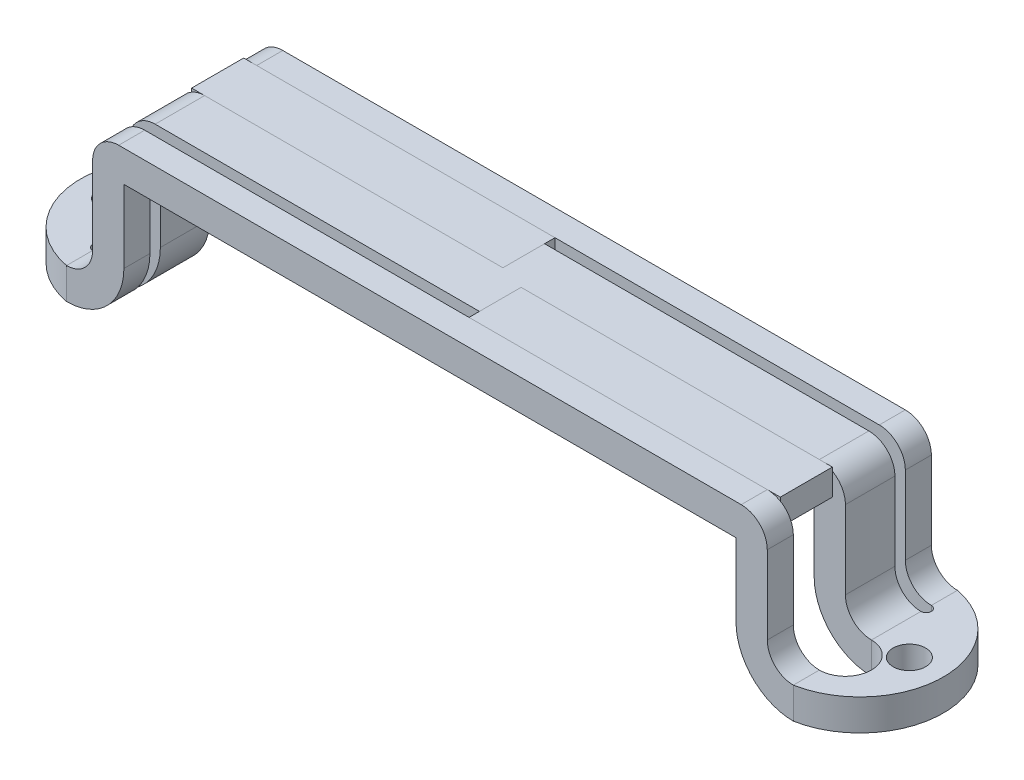
SolidWorks part; units mm, degrees
ref_plane "Front Plane" through (0, 0, 0) normal (0, 0, 1) x (1, 0, 0)
ref_plane "Top Plane" through (0, 0, 0) normal (0, 1, 0) x (1, 0, 0)
ref_plane "Right Plane" through (0, 0, 0) normal (1, 0, 0) x (0, 0, -1)
sketch "Sketch1" plane through (0, 0, 0) normal (0, 0, 1) x (1, 0, 0)
  line L0 (-30.353, 0) -> (30.353, 0)
  line L1 (-32.893, -2.54) -> (-32.893, -10.16)
  line L2 (-35.433, -12.7) -> (-42.0688, -12.7)
  line L3 (0, 0) -> (0, -13.9437) construction
  line L4 (35.433, -12.7) -> (42.0688, -12.7)
  line L5 (32.893, -2.54) -> (32.893, -10.16)
  arc A0 (35.433, -12.7) -> (32.893, -10.16) centre (35.433, -10.16) cw
  arc A1 (30.353, 0) -> (32.893, -2.54) centre (30.353, -2.54) cw
  arc A2 (-30.353, 0) -> (-32.893, -2.54) centre (-30.353, -2.54) ccw
  arc A3 (-32.893, -10.16) -> (-35.433, -12.7) centre (-35.433, -10.16) cw
  point P2 (0, 0)
  point P12 (32.893, -12.7)
  point P15 (32.893, 0)
  point P18 (-32.893, 0)
  point P21 (-32.893, -12.7)
  dimension "D4" = 2.54
  dimension "D1" = 84.1375
  dimension "D2" = 65.786
  dimension "D3" = 12.7
extrude "Extrude-Thin1" add sketch "Sketch1" against normal blind 16.002 thin
sketch "Sketch2" plane through (0, 0, 0) normal (0, 1, 0) x (1, 0, 0)
  line L0 (-35.433, 16.002) -> (-42.0688, 16.002)
  line L1 (-42.0688, 16.002) -> (-42.0688, 0)
  line L2 (-42.0688, 0) -> (-35.433, 0)
  line L3 (35.433, 0) -> (42.0688, 0)
  line L4 (42.0688, 0) -> (42.0688, 16.002)
  line L5 (42.0688, 16.002) -> (35.433, 16.002)
  line L6 (-42.0688, 8.001) -> (-35.433, 8.001) construction
  line L7 (-35.433, 16.002) -> (-35.433, 0) construction
  line L8 (-35.433, 8.001) -> (35.433, 8.001) construction
  line L9 (35.433, 16.002) -> (35.433, 0) construction
  line L10 (35.433, 8.001) -> (42.0688, 8.001) construction
  line L11 (-35.433, 16.002) -> (-35.433, 13.462) construction
  line L12 (-35.433, 13.462) -> (-1.27, 13.462)
  line L13 (-1.27, 13.462) -> (0, 13.462)
  line L14 (0, 0) -> (0, 16.002) construction
  line L15 (-30.353, 16.002) -> (30.353, 16.002) construction
  line L16 (0, 13.462) -> (35.433, 13.462)
  line L17 (35.433, 12.446) -> (-1.27, 12.446)
  line L18 (-35.433, 8.382) -> (-1.27, 8.382)
  line L19 (-1.27, 8.382) -> (-1.27, 12.446)
  line L26 (0, 2.54) -> (-35.433, 2.54)
  line L27 (-35.433, 3.556) -> (1.27, 3.556)
  line L28 (1.27, 2.54) -> (0, 2.54)
  line L29 (1.27, 7.62) -> (1.27, 3.556)
  line L30 (35.433, 2.54) -> (1.27, 2.54)
  line L31 (35.433, 7.62) -> (1.27, 7.62)
  arc A0 (-35.433, 16.002) -> (-35.433, 0) centre (-33.9273, 8.001) ccw
  arc A1 (35.433, 16.002) -> (35.433, 0) centre (33.9273, 8.001) cw
  circle A2 centre (-38.7509, 8.001) radius 1.5875
  circle A3 centre (38.7509, 8.001) radius 1.5875
  arc A4 (35.433, 13.462) -> (35.433, 12.446) centre (35.433, 12.954) cw
  arc A5 (-35.433, 8.382) -> (-35.433, 13.462) centre (-35.433, 10.922) cw
  arc A8 (-35.433, 2.54) -> (-35.433, 3.556) centre (-35.433, 3.048) cw
  arc A9 (35.433, 7.62) -> (35.433, 2.54) centre (35.433, 5.08) cw
  line M4 (30.353, 0) -> (30.353, 16.002)
  line M6 (-30.353, 16.002) -> (-30.353, 0)
  dimension "D1" = 2.54
  dimension "D2" = 1.27
  dimension "D3" = 5.08
  dimension "D4" = 1.016
extrude "Cut-Extrude1" cut sketch "Sketch2" against normal through all contours A0 L0 L1 | A0 L1 L2 | A5 L18 L12 M6 | L18 L19 L17 L16 L13 L12 M4 M6 | L31 L29 L27 L26 L28 L30 M4 M6 | A9 L31 L30 M4 | A3 | L4 A1 L3 | L5 A1 L4 | A4 L16 L17 M4 | A8 L26 L27 M6 | A2
sketch "Sketch3" plane through (0, 0, 0) normal (0, 1, 0) x (1, 0, 0)
  line L0 (-32.893, 13.462) -> (-30.353, 13.462) construction
  line L1 (-1.27, 8.382) -> (-31.623, 8.382)
  line L2 (-1.27, 8.382) -> (-1.27, 13.462)
  line L3 (-1.27, 13.462) -> (-31.623, 13.462)
  line L4 (-31.623, 8.382) -> (-31.623, 13.462)
  line L6 (1.27, 7.62) -> (31.623, 7.62)
  line L7 (1.27, 7.62) -> (1.27, 2.54)
  line L8 (1.27, 2.54) -> (31.623, 2.54)
  line L9 (31.623, 7.62) -> (31.623, 2.54)
  line L10 (32.893, 2.54) -> (30.353, 2.54) construction
extrude "Boss-Extrude1" add sketch "Sketch3" against normal blind 2.54 separate body
sketch "Sketch4" plane through (0, 0, 0) normal (0, 1, 0) x (1, 0, 0)
  line L0 (0, 0) -> (0, 16.002) construction
  line L1 (-30.353, 16.002) -> (30.353, 16.002) construction
  line L21 (-32.893, 17.272) -> (-35.5471, 17.272)
  line L22 (-35.5471, -1.27) -> (-32.893, -1.27)
  line L23 (-32.893, -1.27) -> (-30.353, -1.27)
  line L24 (-30.353, -1.27) -> (30.353, -1.27)
  line L25 (30.353, -1.27) -> (32.893, -1.27)
  line L26 (32.893, -1.27) -> (35.5471, -1.27)
  line L27 (35.5471, 17.272) -> (32.893, 17.272)
  line L28 (32.893, 17.272) -> (30.353, 17.272)
  line L29 (-30.353, 17.272) -> (30.353, 17.272)
  line L30 (-30.353, 17.272) -> (-32.893, 17.272)
  line L32 (-43.3388, 8.001) -> (43.3388, 8.001) construction
  arc A4 (-35.5471, 17.272) -> (-35.5471, -1.27) centre (-33.9273, 8.001) ccw
  arc A5 (35.5471, -1.27) -> (35.5471, 17.272) centre (33.9273, 8.001) ccw
